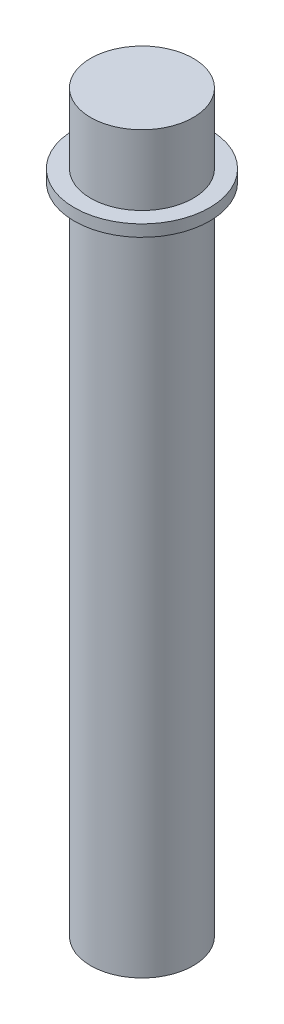
SolidWorks part; units mm, degrees
ref_plane "Front Plane" through (0, 0, 0) normal (0, 0, 1) x (1, 0, 0)
ref_plane "Top Plane" through (0, 0, 0) normal (0, 1, 0) x (1, 0, 0)
ref_plane "Right Plane" through (0, 0, 0) normal (1, 0, 0) x (0, 0, -1)
sketch "Sketch1" plane through (0, 0, 0) normal (0, 1, 0) x (1, 0, 0)
  circle A0 centre (0, 0) radius 2.2
  dimension "D1" = 4.4
extrude "Boss-Extrude1" add sketch "Sketch1" along normal blind 10 and the other way blind 21.5
ref_plane "Plane1" through (0, 7, 0) normal (0, 1, 0) x (1, 0, 0)
sketch "Sketch2" plane through (0, 7, 0) normal (0, 1, 0) x (1, 0, 0)
  circle A0 centre (0, 0) radius 2.9
  circle A1 centre (0, 0) radius 2.2 construction
  circle A2 centre (0, 0) radius 2.2
  dimension "D1" = 5.8
extrude "Boss-Extrude2" add sketch "Sketch2" against normal blind 0.5
